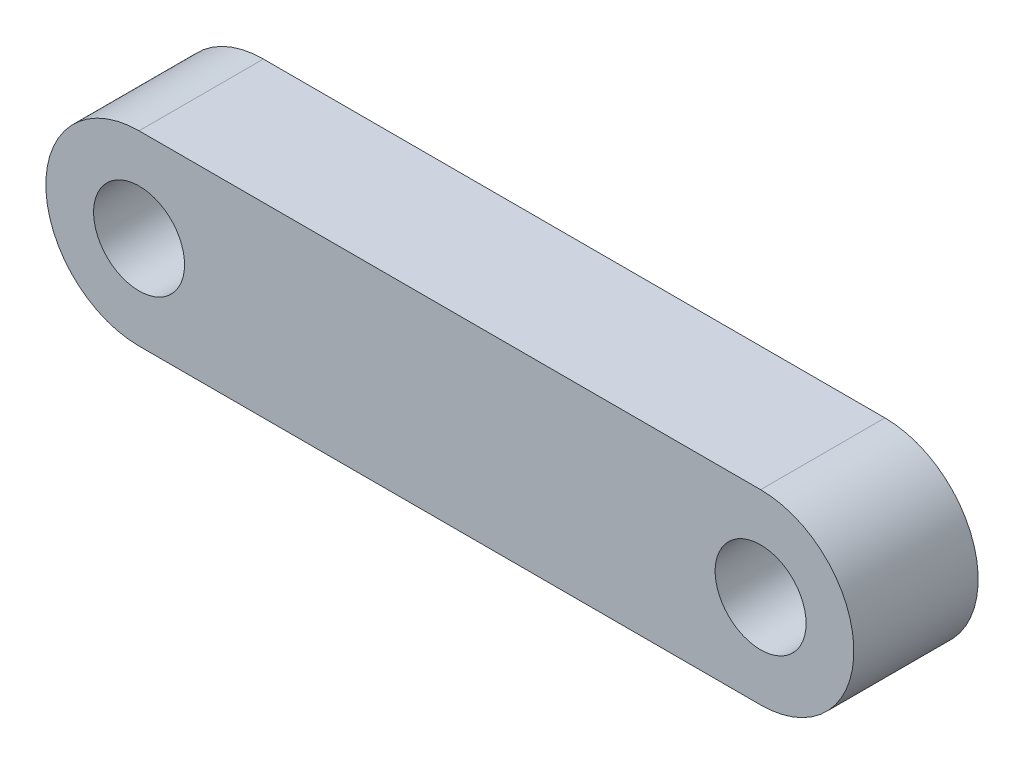
SolidWorks part; units mm, degrees
ref_plane "Front Plane" through (0, 0, 0) normal (0, 0, 1) x (1, 0, 0)
ref_plane "Top Plane" through (0, 0, 0) normal (0, 1, 0) x (1, 0, 0)
ref_plane "Right Plane" through (0, 0, 0) normal (1, 0, 0) x (0, 0, -1)
sketch "Sketch1" plane through (0, 0, 0) normal (0, 0, 1) x (1, 0, 0)
  line L0 (0, 0) -> (50, 0) construction
  line L1 (0, 7.5) -> (50, 7.5)
  line L2 (0, -7.5) -> (50, -7.5)
  arc A0 (0, 7.5) -> (0, -7.5) centre (0, 0) ccw
  arc A1 (50, -7.5) -> (50, 7.5) centre (50, 0) ccw
  circle A2 centre (0, 0) radius 3.6576
  circle A3 centre (50, 0) radius 3.6576
  point P3 (25, 0)
  dimension "D3" = 7.3152
  dimension "D1" = 50
  dimension "D2" = 15
extrude "Boss-Extrude1" add sketch "Sketch1" along normal blind 10
